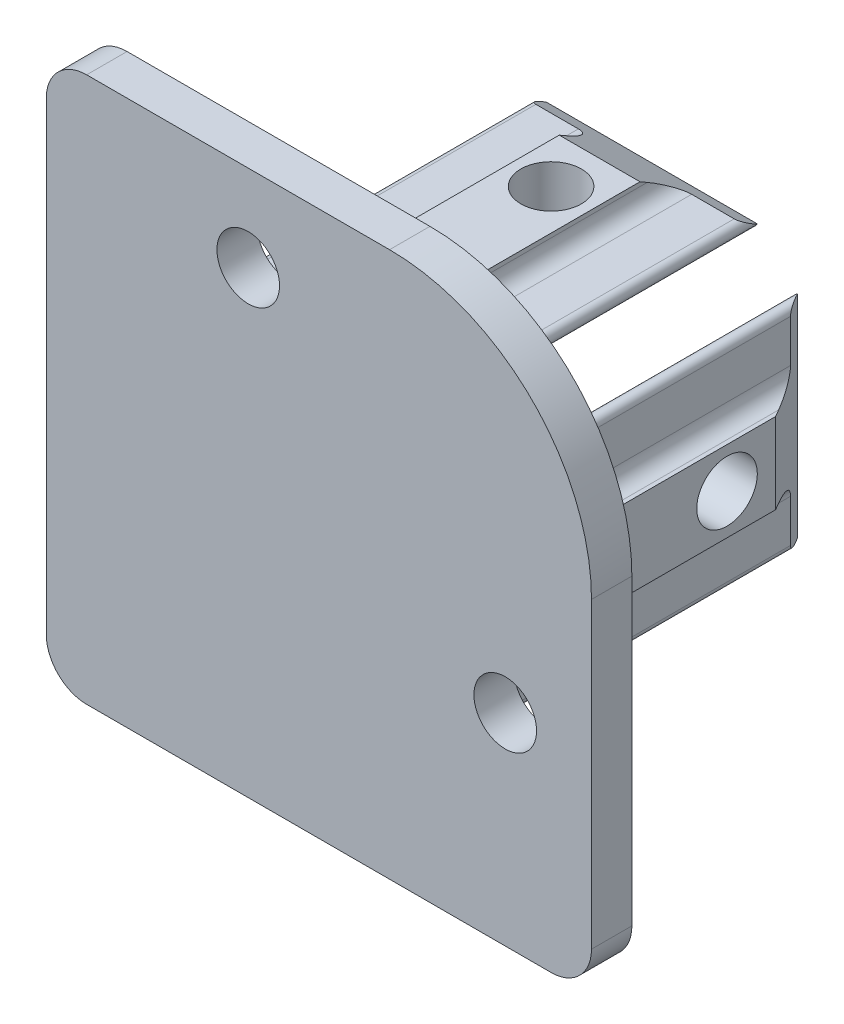
SolidWorks part; units mm, degrees
ref_plane "Front Plane" through (0, 0, 0) normal (0, 0, 1) x (1, 0, 0)
ref_plane "Top Plane" through (0, 0, 0) normal (0, 1, 0) x (1, 0, 0)
ref_plane "Right Plane" through (0, 0, 0) normal (1, 0, 0) x (0, 0, -1)
sketch "Sketch1" plane through (0, 0, 0) normal (0, 0, 1) x (1, 0, 0)
  line L72 (4.9118, -8.2) -> (2.8048, -8.2)
  line L73 (2.5, -8.5048) -> (2.5, -9.2126)
  line L74 (3.2874, -10) -> (8, -10)
  line L75 (10, -8) -> (10, -3.2874)
  line L76 (9.2126, -2.5) -> (8.5048, -2.5)
  line L77 (8.2, -2.8048) -> (8.2, -4.9118)
  line L78 (6.7691, -5.5045) -> (4.4787, -3.2141)
  line L79 (3.6, -1.0928) -> (3.6, 1.0928)
  line L80 (4.4787, 3.2141) -> (6.7691, 5.5045)
  line L81 (8.2, 4.9118) -> (8.2, 2.8048)
  line L82 (8.5048, 2.5) -> (9.2126, 2.5)
  line L83 (10, 3.2874) -> (10, 8)
  line L84 (8, 10) -> (3.2874, 10)
  line L85 (2.5, 9.2126) -> (2.5, 8.5048)
  line L86 (2.8048, 8.2) -> (4.9118, 8.2)
  line L87 (5.5045, 6.7691) -> (3.2141, 4.4787)
  line L88 (1.0928, 3.6) -> (-1.0928, 3.6)
  line L89 (-3.2141, 4.4787) -> (-5.5045, 6.7691)
  line L90 (-4.9118, 8.2) -> (-2.8048, 8.2)
  line L91 (-2.5, 8.5048) -> (-2.5, 9.2126)
  line L92 (-3.2874, 10) -> (-8, 10)
  line L93 (-10, 8) -> (-10, 3.2874)
  line L94 (-9.2126, 2.5) -> (-8.5048, 2.5)
  line L95 (-8.2, 2.8048) -> (-8.2, 4.9118)
  line L96 (-6.7691, 5.5045) -> (-4.4787, 3.2141)
  line L97 (-3.6, 1.0928) -> (-3.6, -1.0928)
  line L98 (-4.4787, -3.2141) -> (-6.7691, -5.5045)
  line L99 (-8.2, -4.9118) -> (-8.2, -2.8048)
  line L100 (-8.5048, -2.5) -> (-9.2126, -2.5)
  line L101 (-10, -3.2874) -> (-10, -8)
  line L102 (-8, -10) -> (-3.2874, -10)
  line L103 (-2.5, -9.2126) -> (-2.5, -8.5048)
  line L104 (-2.8048, -8.2) -> (-4.9118, -8.2)
  line L105 (-5.5045, -6.7691) -> (-3.2141, -4.4787)
  line L106 (-1.0928, -3.6) -> (1.0928, -3.6)
  line L107 (3.2141, -4.4787) -> (5.5045, -6.7691)
  circle A2 centre (0, 0) radius 2.15
  arc A74 (4.9118, -8.2) -> (5.5045, -6.7691) centre (4.9118, -7.3618) ccw
  arc A75 (2.8048, -8.2) -> (2.5, -8.5048) centre (2.8048, -8.5048) ccw
  arc A76 (2.5, -9.2126) -> (3.2874, -10) centre (3.2874, -9.2126) ccw
  arc A77 (8, -10) -> (10, -8) centre (8, -8) ccw
  arc A78 (10, -3.2874) -> (9.2126, -2.5) centre (9.2126, -3.2874) ccw
  arc A79 (8.5048, -2.5) -> (8.2, -2.8048) centre (8.5048, -2.8048) ccw
  arc A80 (6.7691, -5.5045) -> (8.2, -4.9118) centre (7.3618, -4.9118) ccw
  arc A81 (3.6, -1.0928) -> (4.4787, -3.2141) centre (6.6, -1.0928) ccw
  arc A82 (4.4787, 3.2141) -> (3.6, 1.0928) centre (6.6, 1.0928) ccw
  arc A83 (8.2, 4.9118) -> (6.7691, 5.5045) centre (7.3618, 4.9118) ccw
  arc A84 (8.2, 2.8048) -> (8.5048, 2.5) centre (8.5048, 2.8048) ccw
  arc A85 (9.2126, 2.5) -> (10, 3.2874) centre (9.2126, 3.2874) ccw
  arc A86 (10, 8) -> (8, 10) centre (8, 8) ccw
  arc A87 (3.2874, 10) -> (2.5, 9.2126) centre (3.2874, 9.2126) ccw
  arc A88 (2.5, 8.5048) -> (2.8048, 8.2) centre (2.8048, 8.5048) ccw
  arc A89 (5.5045, 6.7691) -> (4.9118, 8.2) centre (4.9118, 7.3618) ccw
  arc A90 (1.0928, 3.6) -> (3.2141, 4.4787) centre (1.0928, 6.6) ccw
  arc A91 (-3.2141, 4.4787) -> (-1.0928, 3.6) centre (-1.0928, 6.6) ccw
  arc A92 (-4.9118, 8.2) -> (-5.5045, 6.7691) centre (-4.9118, 7.3618) ccw
  arc A93 (-2.8048, 8.2) -> (-2.5, 8.5048) centre (-2.8048, 8.5048) ccw
  arc A94 (-2.5, 9.2126) -> (-3.2874, 10) centre (-3.2874, 9.2126) ccw
  arc A95 (-8, 10) -> (-10, 8) centre (-8, 8) ccw
  arc A96 (-10, 3.2874) -> (-9.2126, 2.5) centre (-9.2126, 3.2874) ccw
  arc A97 (-8.5048, 2.5) -> (-8.2, 2.8048) centre (-8.5048, 2.8048) ccw
  arc A98 (-6.7691, 5.5045) -> (-8.2, 4.9118) centre (-7.3618, 4.9118) ccw
  arc A99 (-3.6, 1.0928) -> (-4.4787, 3.2141) centre (-6.6, 1.0928) ccw
  arc A100 (-4.4787, -3.2141) -> (-3.6, -1.0928) centre (-6.6, -1.0928) ccw
  arc A101 (-8.2, -4.9118) -> (-6.7691, -5.5045) centre (-7.3618, -4.9118) ccw
  arc A102 (-8.2, -2.8048) -> (-8.5048, -2.5) centre (-8.5048, -2.8048) ccw
  arc A103 (-9.2126, -2.5) -> (-10, -3.2874) centre (-9.2126, -3.2874) ccw
  arc A104 (-10, -8) -> (-8, -10) centre (-8, -8) ccw
  arc A105 (-3.2874, -10) -> (-2.5, -9.2126) centre (-3.2874, -9.2126) ccw
  arc A106 (-2.5, -8.5048) -> (-2.8048, -8.2) centre (-2.8048, -8.5048) ccw
  arc A107 (-5.5045, -6.7691) -> (-4.9118, -8.2) centre (-4.9118, -7.3618) ccw
  arc A108 (-1.0928, -3.6) -> (-3.2141, -4.4787) centre (-1.0928, -6.6) ccw
  arc A109 (3.2141, -4.4787) -> (1.0928, -3.6) centre (1.0928, -6.6) ccw
sketch "Sketch2" plane through (0, 0, 0) normal (0, 0, 1) x (1, 0, 0)
  line L0 (-2.5, 9.2126) -> (2.5, 9.2126)
  line L1 (2.5, 9.2126) -> (2.5, 8.5048) construction
  line L2 (2.8048, 8.2) -> (4.9118, 8.2) construction
  line L3 (5.5045, 6.7691) -> (3.2141, 4.4787) construction
  line L4 (1.0928, 3.6) -> (-1.0928, 3.6) construction
  line L5 (-3.2141, 4.4787) -> (-5.5045, 6.7691) construction
  line L6 (-4.9118, 8.2) -> (-2.8048, 8.2) construction
  line L7 (-2.5, 8.5048) -> (-2.5, 9.2126) construction
  line L8 (2.5, 9.2126) -> (2.5, 8.5048)
  line L9 (2.8048, 8.2) -> (4.9118, 8.2)
  line L10 (5.5045, 6.7691) -> (3.2141, 4.4787)
  line L11 (1.0928, 3.6) -> (-1.0928, 3.6)
  line L12 (-3.2141, 4.4787) -> (-5.5045, 6.7691)
  line L13 (-4.9118, 8.2) -> (-2.8048, 8.2)
  line L14 (-2.5, 8.5048) -> (-2.5, 9.2126)
  line L15 (-2.8605, 4.8322) -> (-5.1509, 7.1227)
  line L16 (-4.9118, 7.7) -> (-2.8048, 7.7)
  line L17 (-2, 8.5048) -> (-2, 8.7126)
  line L18 (-2, 8.7126) -> (2, 8.7126)
  line L19 (2, 8.7126) -> (2, 8.5048)
  line L20 (2.8048, 7.7) -> (4.9118, 7.7)
  line L21 (5.1509, 7.1227) -> (2.8605, 4.8322)
  line L22 (1.0928, 4.1) -> (-1.0928, 4.1)
  arc A0 (2.5, 8.5048) -> (2.8048, 8.2) centre (2.8048, 8.5048) ccw construction
  arc A1 (5.5045, 6.7691) -> (4.9118, 8.2) centre (4.9118, 7.3618) ccw construction
  arc A2 (1.0928, 3.6) -> (3.2141, 4.4787) centre (1.0928, 6.6) ccw construction
  arc A3 (-3.2141, 4.4787) -> (-1.0928, 3.6) centre (-1.0928, 6.6) ccw construction
  arc A4 (-4.9118, 8.2) -> (-5.5045, 6.7691) centre (-4.9118, 7.3618) ccw construction
  arc A5 (-2.8048, 8.2) -> (-2.5, 8.5048) centre (-2.8048, 8.5048) ccw construction
  arc A6 (2.5, 8.5048) -> (2.8048, 8.2) centre (2.8048, 8.5048) ccw
  arc A7 (5.5045, 6.7691) -> (4.9118, 8.2) centre (4.9118, 7.3618) ccw
  arc A8 (1.0928, 3.6) -> (3.2141, 4.4787) centre (1.0928, 6.6) ccw
  arc A9 (-3.2141, 4.4787) -> (-1.0928, 3.6) centre (-1.0928, 6.6) ccw
  arc A10 (-4.9118, 8.2) -> (-5.5045, 6.7691) centre (-4.9118, 7.3618) ccw
  arc A11 (-2.8048, 8.2) -> (-2.5, 8.5048) centre (-2.8048, 8.5048) ccw
  arc A12 (-4.9118, 7.7) -> (-5.1509, 7.1227) centre (-4.9118, 7.3618) ccw
  arc A13 (-2.8048, 7.7) -> (-2, 8.5048) centre (-2.8048, 8.5048) ccw
  arc A14 (2, 8.5048) -> (2.8048, 7.7) centre (2.8048, 8.5048) ccw
  arc A15 (5.1509, 7.1227) -> (4.9118, 7.7) centre (4.9118, 7.3618) ccw
  arc A16 (1.0928, 4.1) -> (2.8605, 4.8322) centre (1.0928, 6.6) ccw
  arc A17 (-2.8605, 4.8322) -> (-1.0928, 4.1) centre (-1.0928, 6.6) ccw
  dimension "D1" = 0.5
extrude "Boss-Extrude2" add sketch "Sketch2" against normal blind 20 contours L22 A17 L15 A12 L16 A13 L17 L18 L19 A14 L20 A15 L21 A16
chamfer "Chamfer2" distance 1.5 angle 60 1 edges at (0, 8.7126, -20)
sketch "Sketch4" plane through (0, 8.7126, 0) normal (0, 1, 0) x (1, 0, 0)
  line L0 (0, 0) -> (0, 20) construction
  line L1 (-2, 20) -> (2, 20) construction
  line L2 (-3.2141, 0) -> (-1.0928, 0) construction
  circle A0 centre (0, 15) radius 1.5
  dimension "D1" = 3
  dimension "D2" = 15
extrude "Cut-Extrude1" cut sketch "Sketch4" against normal through all contours A0
sketch "Sketch5" plane through (0, 0, 0) normal (0, 0, 1) x (1, 0, 0)
  line L0 (-2, 8.7126) -> (-2, 16)
  line L1 (0, 0) -> (16, 16)
  line L3 (-2, 16) -> (16, 16)
  line L5 (10.5, 10.5) -> (2, 10.5)
  line L6 (2, 10.5) -> (2, 8.7126)
  line L7 (8, 10) -> (3.2874, 10) construction
  line L8 (2.8605, 4.8322) -> (5.1509, 7.1227)
  line L9 (4.9118, 7.7) -> (2.8048, 7.7)
  line L10 (2, 8.5048) -> (2, 8.7126)
  line L11 (2, 8.7126) -> (-2, 8.7126)
  line L12 (-2, 8.7126) -> (-2, 8.5048)
  line L13 (-2.8048, 7.7) -> (-4.9118, 7.7)
  line L14 (-5.1509, 7.1227) -> (-2.8605, 4.8322)
  line L15 (-1.0928, 4.1) -> (1.0928, 4.1)
  line L16 (2.8605, 4.8322) -> (5.1509, 7.1227)
  line L17 (4.9118, 7.7) -> (2.8048, 7.7)
  line L18 (2, 8.5048) -> (2, 8.7126)
  line L19 (2, 8.7126) -> (-2, 8.7126)
  line L20 (-2, 8.7126) -> (-2, 8.5048)
  line L21 (-2.8048, 7.7) -> (-4.9118, 7.7)
  line L22 (-5.1509, 7.1227) -> (-2.8605, 4.8322)
  line L23 (-1.0928, 4.1) -> (1.0928, 4.1)
  arc A6 (1.0928, 4.1) -> (2.8605, 4.8322) centre (1.0928, 6.6) ccw
  arc A7 (5.1509, 7.1227) -> (4.9118, 7.7) centre (4.9118, 7.3618) ccw
  arc A8 (2, 8.5048) -> (2.8048, 7.7) centre (2.8048, 8.5048) ccw
  arc A9 (-2.8048, 7.7) -> (-2, 8.5048) centre (-2.8048, 8.5048) ccw
  arc A10 (-4.9118, 7.7) -> (-5.1509, 7.1227) centre (-4.9118, 7.3618) ccw
  arc A11 (-2.8605, 4.8322) -> (-1.0928, 4.1) centre (-1.0928, 6.6) ccw
  arc A12 (1.0928, 4.1) -> (2.8605, 4.8322) centre (1.0928, 6.6) ccw
  arc A13 (5.1509, 7.1227) -> (4.9118, 7.7) centre (4.9118, 7.3618) ccw
  arc A14 (2, 8.5048) -> (2.8048, 7.7) centre (2.8048, 8.5048) ccw
  arc A15 (-2.8048, 7.7) -> (-2, 8.5048) centre (-2.8048, 8.5048) ccw
  arc A16 (-4.9118, 7.7) -> (-5.1509, 7.1227) centre (-4.9118, 7.3618) ccw
  arc A17 (-2.8605, 4.8322) -> (-1.0928, 4.1) centre (-1.0928, 6.6) ccw
  line M26 (2, 8.7126) -> (-2, 8.7126)
  dimension "D2" = 0.5
  dimension "D3" = 16
  dimension "D1" = 0
extrude "Boss-Extrude3" [suppressed] add sketch "Sketch5" against normal blind 2.5 contours L6 L5 L1 L3 L0 M26
sketch "Sketch6" plane through (0, 0, 0) normal (0, 0, 1) x (1, 0, 0)
  line L1 (-10, 17) -> (17, 17)
  line L2 (-10, 17) -> (-10, -10)
  line L3 (-10, -10) -> (17, -10)
  line L4 (17, 17) -> (17, -10)
  line L5 (-10, 8) -> (-10, 3.2874) construction
  line L7 (3.2874, -10) -> (8, -10) construction
  dimension "D1" = 17
  dimension "D2" = 17
extrude "Boss-Extrude4" add sketch "Sketch6" against normal blind 2
sketch "Sketch9" plane through (0, 0, 0) normal (1, 0, 0) x (0, 0, -1)
  line L0 (0, 0) -> (10.8044, 0) construction
pattern_circular "CirPattern1" count 4 over 360 about axis through (0, 0, 0) along (0, 0, 1) of "Boss-Extrude2", "Cut-Extrude1", "Chamfer2"
sketch "Sketch10" plane through (0, 0, 0) normal (0, 0, 1) x (1, 0, 0)
  line L0 (-10, -10) -> (17, 17) construction
  line L2 (0, 0) -> (12.7279, 0) construction
  circle A0 centre (0, 12.7279) radius 1.55
  circle A1 centre (12.7279, 0) radius 1.55
  dimension "D2" = 3.1
  dimension "D1" = 18
extrude "Cut-Extrude3" cut sketch "Sketch10" against normal through all
fillet "Fillet1" radius 10 1 edges at (17, 17, -1)
fillet "Fillet2" radius 2 3 edges at (-10, 17, -1) (-10, -10, -1) (17, -10, -1)
